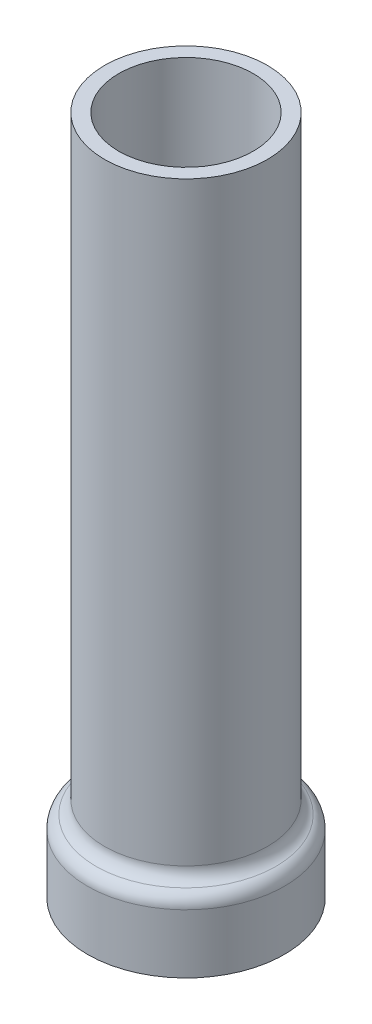
SolidWorks part; units mm, degrees
ref_plane "Front Plane" through (0, 0, 0) normal (0, 0, 1) x (1, 0, 0)
ref_plane "Top Plane" through (0, 0, 0) normal (0, 1, 0) x (1, 0, 0)
ref_plane "Right Plane" through (0, 0, 0) normal (1, 0, 0) x (0, 0, -1)
sketch "Sketch1" plane through (0, 0, 0) normal (0, 1, 0) x (1, 0, 0)
  circle A0 centre (0, 0) radius 15.113
  circle A1 centre (0, 0) radius 17.653
  dimension "D1" = 30.226
  dimension "D2" = 2.54
extrude "Boss-Extrude1" add sketch "Sketch1" along normal blind 6.35
sketch "Sketch2" plane through (0, 6.35, 0) normal (0, 1, 0) x (1, 0, 0)
  circle A0 centre (0, 0) radius 12.065
  circle A1 centre (0, 0) radius 17.653
  circle A2 centre (0, 0) radius 17.653 construction
  dimension "D1" = 24.13
extrude "Boss-Extrude2" add sketch "Sketch2" along normal blind 6.35
sketch "Sketch3" plane through (0, 12.7, 0) normal (0, 1, 0) x (1, 0, 0)
  circle A0 centre (0, 0) radius 12.065
  circle A1 centre (0, 0) radius 14.605
  dimension "D1" = 24.13
  dimension "D2" = 2.54
extrude "Boss-Extrude3" add sketch "Sketch3" along normal blind 109.22
fillet "Fillet1" radius 2.54 1 edges at (0, 12.7, 14.605)
fillet "Fillet2" radius 2.54 1 edges at (0, 12.7, 17.653)
